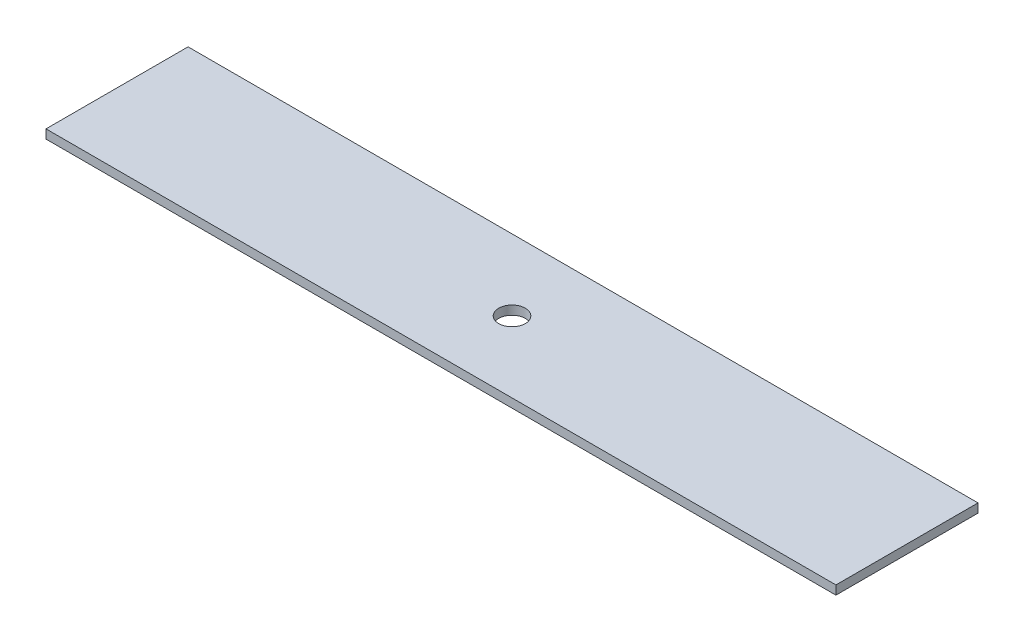
SolidWorks part; units mm, degrees
ref_plane "Front Plane" through (0, 0, 0) normal (0, 0, 1) x (1, 0, 0)
ref_plane "Top Plane" through (0, 0, 0) normal (0, 1, 0) x (1, 0, 0)
ref_plane "Right Plane" through (0, 0, 0) normal (1, 0, 0) x (0, 0, -1)
sketch "Sketch1" plane through (0, 0, 0) normal (0, 1, 0) x (1, 0, 0)
  line L1 (-141.224, 25.4) -> (141.224, 25.4)
  line L2 (-141.224, 25.4) -> (-141.224, -25.4)
  line L3 (-141.224, -25.4) -> (141.224, -25.4)
  line L4 (141.224, 25.4) -> (141.224, -25.4)
  line L5 (-141.224, 25.4) -> (141.224, -25.4) construction
  line L6 (-141.224, -25.4) -> (141.224, 25.4) construction
  point P0 (0, 0)
  dimension "D1" = 282.448
extrude "Boss-Extrude1" add sketch "Sketch1" along normal blind 3.175
sketch "Sketch2" plane through (0, 3.175, 0) normal (0, 1, 0) x (1, 0, 0)
  circle A0 centre (0, 0) radius 4.7625
extrude "Cut-Extrude1" cut sketch "Sketch2" against normal up to next
